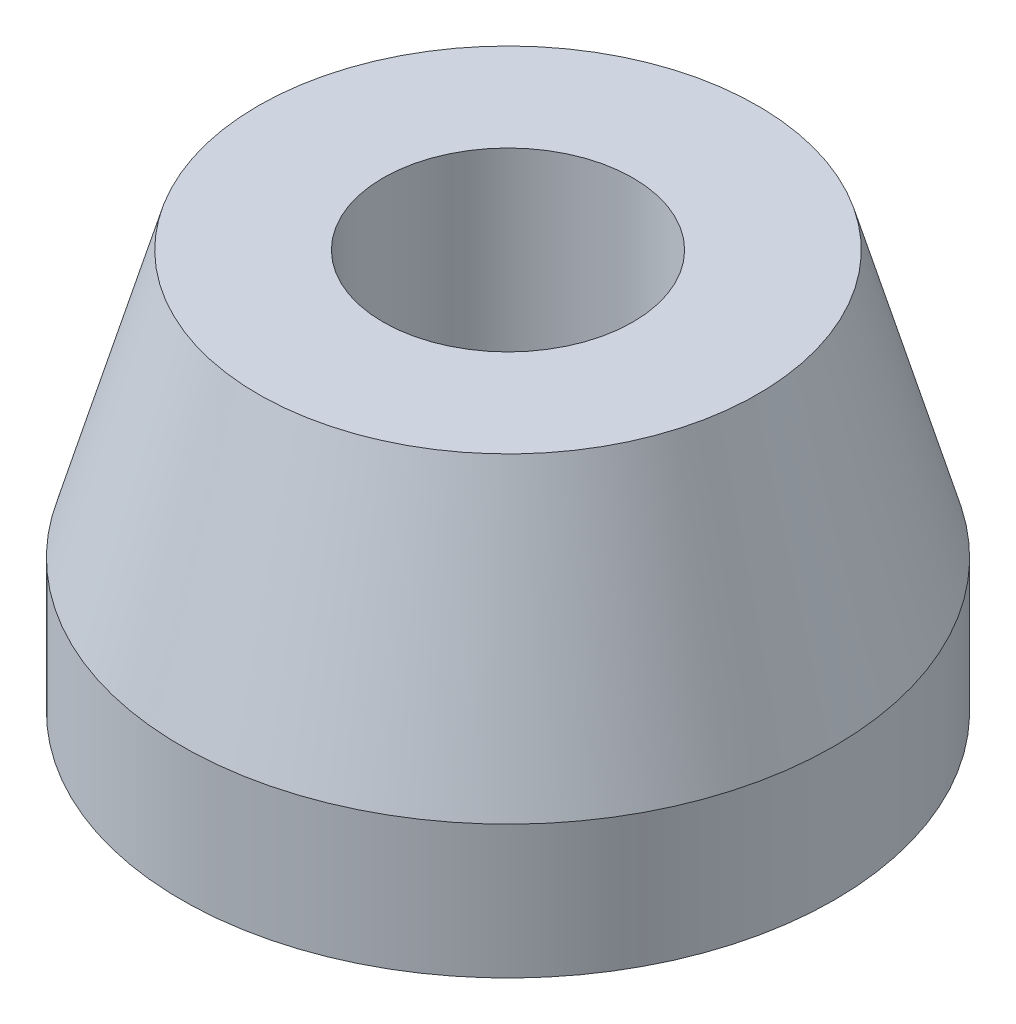
SolidWorks part; units mm, degrees
ref_plane "Front Plane" through (0, 0, 0) normal (0, 0, 1) x (1, 0, 0)
ref_plane "Top Plane" through (0, 0, 0) normal (0, 1, 0) x (1, 0, 0)
ref_plane "Right Plane" through (0, 0, 0) normal (1, 0, 0) x (0, 0, -1)
sketch "Sketch1" plane through (0, 0, 0) normal (0, 0, 1) x (1, 0, 0)
  line L0 (0, 0) -> (-12.446, 0)
  line L1 (-12.446, 0) -> (-12.446, 5.08)
  line L2 (-12.446, 5.08) -> (-9.525, 15.24)
  line L3 (-9.525, 15.24) -> (0, 15.24)
  line L4 (0, 15.24) -> (0, 0)
  dimension "D1" = 5.08
  dimension "D2" = 15.24
  dimension "D3" = 9.525
  dimension "D4" = 12.446
revolve "Revolve1" add sketch "Sketch1" angle 360 about L4
sketch "Sketch2" plane through (0, 15.24, 0) normal (0, 1, 0) x (1, 0, 0)
  circle A0 centre (0, 0) radius 4.7625
  dimension "D1" = 9.525
extrude "Cut-Extrude1" cut sketch "Sketch2" against normal through all both and the other way through all
equation "\"OldSchoolLengthHoles\"= 2.5in'OldSchool > NewSchool"
equation "\"SchoolWidthHoles\"= 1.625in'OldSchool = NewSchool"
equation "\"Angle\"= 40deg'Looks about <= 40deg"
equation "\"Width\"= 2.125in'Pretty sure this is standardized on longboard and skateboard"
equation "\"Length\"= 3in'Will have some variation?"
equation "\"NewSchoolLengthHoles\"= 2.125in'NewSchool Mounting"
equation "\"HoleSize\"= ( 3in / 16 )'hole"
equation "\"Depth\"= 1in / 8'Assuming same depth as a riserplate"
equation "\"KingpinBoltSize\"= 3in / 8"
equation "\"PivotCupDia\"= 0.63in'0.7in (large) 0.626 (small)"
equation "\"PivotCupDepth\"= 12mm'15mm (large) 12mm (small)"
equation "\"PivotCupEndAngle\"= 18deg'Don't Know looks like (I don't even think I used this)"
equation "\"PivotCupInnerDia\"= 0.43in'0.5in (large) 0.43 (small)"
equation "\"BushingDia\"= .98in"
equation "\"BusingDepth\"= .6in"
equation "\"BushingSmallDia\"= .75in"
equation "\"D1@Sketch1\"=\"BusingDepth\"/3"
equation "\"D2@Sketch1\"=\"BusingDepth\""
equation "\"D3@Sketch1\"=\"BushingSmallDia\"/2"
equation "\"D4@Sketch1\"=\"BushingDia\"/2"
equation "\"D1@Sketch2\"=\"KingpinBoltSize\""
